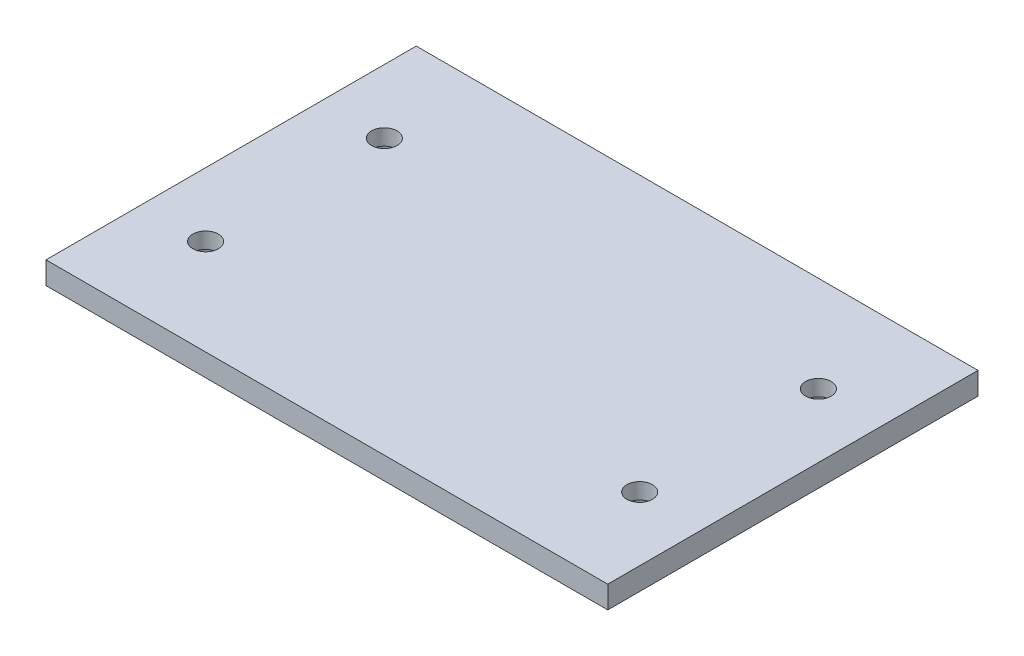
SolidWorks part; units mm, degrees
ref_plane "Front Plane" through (0, 0, 0) normal (0, 0, 1) x (1, 0, 0)
ref_plane "Top Plane" through (0, 0, 0) normal (0, 1, 0) x (1, 0, 0)
ref_plane "Right Plane" through (0, 0, 0) normal (1, 0, 0) x (0, 0, -1)
sketch "Sketch1" plane through (0, 0, 0) normal (0, 1, 0) x (1, 0, 0)
  line L1 (-440, 290) -> (440, 290)
  line L2 (-440, 290) -> (-440, -290)
  line L3 (-440, -290) -> (440, -290)
  line L4 (440, 290) -> (440, -290)
  line L6 (-440, 0) -> (440, 0) construction
  point P0 (0, 0)
extrude "Boss-Extrude1" add sketch "Sketch1" along normal blind 35
sketch "Sketch2" plane through (0, 0, 0) normal (0, -1, 0) x (1, 0, 0)
  circle A0 centre (-340, 140) radius 20
  circle A1 centre (340, 140) radius 20
  circle A2 centre (340, -140) radius 20
  circle A3 centre (-340, -140) radius 20
  dimension "D1" = 680
  dimension "D2" = 140
  dimension "D3" = 340
extrude "Cut-Extrude1" cut sketch "Sketch2" against normal blind 202
sketch "Sketch3" plane through (0, 0, 0) normal (0, -1, 0) x (1, 0, 0)
  circle A0 centre (-340, 140) radius 25
  circle A1 centre (340, 140) radius 25
  circle A2 centre (340, -140) radius 25
  circle A3 centre (-340, -140) radius 25
extrude "Cut-Extrude2" cut sketch "Sketch3" against normal blind 10
